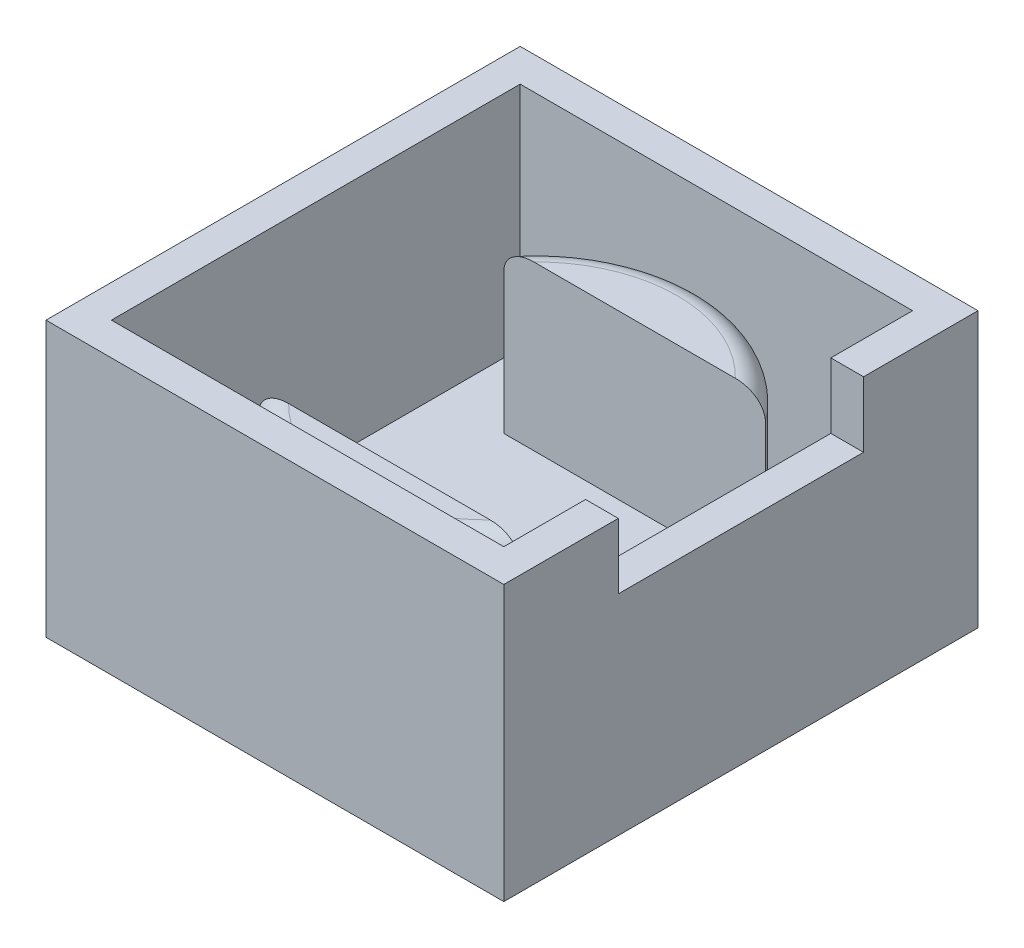
SolidWorks part; units mm, degrees
ref_plane "Front Plane" through (0, 0, 0) normal (0, 0, 1) x (1, 0, 0)
ref_plane "Top Plane" through (0, 0, 0) normal (0, 1, 0) x (1, 0, 0)
ref_plane "Right Plane" through (0, 0, 0) normal (1, 0, 0) x (0, 0, -1)
sketch "Sketch1" plane through (0, 0, 0) normal (0, 1, 0) x (1, 0, 0)
  line L1 (0, 0) -> (30.48, 0)
  line L2 (0, 0) -> (0, 31.75)
  line L3 (0, 31.75) -> (30.48, 31.75)
  line L4 (30.48, 0) -> (30.48, 31.75)
  dimension "D1" = 31.75
  dimension "D2" = 30.48
extrude "Boss-Extrude1" add sketch "Sketch1" along normal blind 3.556
sketch "Sketch2" plane through (0, 3.556, 0) normal (0, 1, 0) x (1, 0, 0)
  line L0 (0, 31.75) -> (0, 0) construction
  line L1 (0, 25.4) -> (30.48, 25.4)
  line L2 (0, 25.4) -> (0, 6.35)
  line L3 (0, 6.35) -> (30.48, 6.35)
  line L4 (30.48, 25.4) -> (30.48, 6.35)
  line L5 (30.48, 0) -> (30.48, 31.75) construction
  line L6 (30.48, 25.4) -> (30.48, 31.75) construction
  line L7 (30.48, 0) -> (30.48, 6.35) construction
  line L8 (0, 15.875) -> (30.48, 15.875) construction
  arc A0 (5.08, 25.4) -> (25.4, 25.4) centre (15.24, 17.78) cw
  arc A1 (5.08, 6.35) -> (25.4, 6.35) centre (15.24, 13.97) ccw
  dimension "D1" = 19.05
  dimension "D2" = 7.62
extrude "Boss-Extrude2" add sketch "Sketch2" along normal blind 12.7 contours L3 A1 | A0 L1
sketch "Sketch4" plane through (0, 3.556, 0) normal (0, 1, 0) x (1, 0, 0)
  line L0 (0, 31.75) -> (0, 0) construction
  line L1 (-1.778, 33.528) -> (67.818, 33.528)
  line L2 (-1.778, 33.528) -> (-1.778, -39.878)
  line L3 (-1.778, -39.878) -> (67.818, -39.878)
  line L4 (67.818, 33.528) -> (67.818, -39.878)
  line L5 (30.48, 31.75) -> (0, 31.75) construction
  line L7 (0, 31.75) -> (66.04, 31.75)
  line L8 (0, 31.75) -> (0, -38.1)
  line L9 (0, -38.1) -> (66.04, -38.1)
  line L10 (66.04, 31.75) -> (66.04, -38.1)
  line L12 (17.145, -38.1) -> (17.145, -7.62)
  line L13 (17.145, -7.62) -> (48.895, -7.62)
  line L14 (48.895, -7.62) -> (48.895, -38.1)
  line L15 (33.02, -38.1) -> (33.02, 16.283) construction
  dimension "D1" = 69.596
  dimension "D2" = 73.406
  dimension "D3" = 1.778
  dimension "D4" = 1.778
  dimension "D5" = 1.778
  dimension "D6" = 1.778
  dimension "D7" = 15.875
  dimension "D8" = 15.875
  dimension "D9" = 30.48
extrude "Boss-Extrude3" add sketch "Sketch4" against normal blind 3.556
sketch "Sketch8" plane through (0, 3.556, 0) normal (0, 1, 0) x (1, 0, 0)
  line L0 (0, 31.75) -> (0, 27.178)
  line L1 (0, 0) -> (0, 31.75) construction
  line L2 (0, 27.178) -> (0, 4.572)
  line L3 (-1.778, 27.178) -> (-1.778, 33.528)
  line L4 (-1.778, 33.528) -> (32.258, 33.528)
  line L5 (32.258, 33.528) -> (32.258, -1.778)
  line L6 (32.258, -1.778) -> (-1.778, -1.778)
  line L7 (-1.778, -1.778) -> (-1.778, 4.572)
  line L8 (-1.778, 4.572) -> (-1.778, 27.178)
  line L9 (0, 4.572) -> (0, 0)
  line L10 (0, 0) -> (30.48, 0)
  line L11 (30.48, 0) -> (30.48, 31.75)
  line L12 (30.48, 31.75) -> (0, 31.75)
  dimension "D1" = 1.778
  dimension "D2" = 1.778
  dimension "D3" = 1.778
  dimension "D4" = 1.778
  dimension "D5" = 1.778
  dimension "D6" = 6.35
  dimension "D7" = 6.35
extrude "Boss-Extrude5" add sketch "Sketch8" along normal blind 12.7 contours L5 L6 L7 L9 L10 L11 L12 L0 L3 L4
ref_plane "Plane2" through (0, 0, 3.175) normal (0, 0, -1) x (-1, 0, 0)
ref_plane "Plane1" through (33.02, 0, 0) normal (1, 0, 0) x (0, 0, -1)
mirror "Mirror1" about plane through (0, 0, 3.175) normal (0, 0, -1) of "Boss-Extrude5"
mirror "Mirror2" about plane through (33.02, 0, 0) normal (1, 0, 0) of "Mirror1", "Boss-Extrude5"
mirror "Mirror3" about plane through (0, 0, 3.175) normal (0, 0, -1) of "Boss-Extrude2"
mirror "Mirror4" about plane through (33.02, 0, 0) normal (1, 0, 0) of "Mirror3", "Boss-Extrude2"
fillet "Fillet5" radius 1.778 8 edges at (50.8, 16.256, 36.83) (15.24, 16.256, 36.83) (15.24, 16.256, 7.62) (15.24, 16.256, -1.27) (15.24, 16.256, -30.48) (50.8, 16.256, -30.48) (50.8, 16.256, -1.27) (50.8, 16.256, 7.62)
sketch "Sketch9" plane through (0, 16.256, 0) normal (0, 1, 0) x (1, 0, 0)
  line L1 (32.258, 33.528) -> (33.782, 33.528)
  line L2 (32.258, 33.528) -> (32.258, -39.878)
  line L3 (32.258, -39.878) -> (33.782, -39.878)
  line L4 (33.782, 33.528) -> (33.782, -39.878)
  line L5 (-1.778, -1.778) -> (67.818, -1.778)
  line L6 (-1.778, -1.778) -> (-1.778, -4.572)
  line L7 (-1.778, -4.572) -> (67.818, -4.572)
  line L8 (67.818, -1.778) -> (67.818, -4.572)
  line M47 (-1.778, -1.778) -> (32.258, -1.778)
  line M48 (32.258, -1.778) -> (32.258, 33.528)
extrude "Boss-Extrude7" add sketch "Sketch9" against normal up to body contours L5 L4 L1 M48 | L7 L2 L3 L4 | L2 L7 L4 L5 | L8 L5 L4 L7 | L6 L7 L2 M47
sketch "Sketch10" plane through (0, 16.256, 0) normal (0, 1, 0) x (1, 0, 0)
  line L0 (67.818, -4.572) -> (33.782, -4.572)
  line L1 (67.818, -39.878) -> (67.818, 33.528) construction
  line L2 (33.782, -4.572) -> (33.782, -39.878)
  line L3 (67.818, -39.878) -> (-1.778, -39.878) construction
  line L4 (33.782, -39.878) -> (-10.0613, -39.878)
  line L5 (-10.0613, -39.878) -> (-10.0613, 34.6908)
  line L6 (-10.0613, 34.6908) -> (71.0188, 34.6908)
  line L7 (71.0188, 34.6908) -> (71.0188, -4.572)
  line L8 (71.0188, -4.572) -> (67.818, -4.572)
  line L9 (35.56, -6.35) -> (35.56, -38.1) construction
  line L10 (66.04, -6.35) -> (35.56, -6.35) construction
  dimension "D1" = 1.778
  dimension "D2" = 1.778
extrude "Cut-Extrude1" cut sketch "Sketch10" against normal through all
sketch "Sketch11" plane through (0, 16.256, 0) normal (0, 1, 0) x (1, 0, 0)
  line L0 (33.02, -3.81) -> (33.02, -40.64)
  line L1 (33.782, -4.572) -> (67.818, -4.572)
  line L2 (33.782, -4.572) -> (33.782, -39.878)
  line L3 (33.782, -39.878) -> (67.818, -39.878)
  line L4 (67.818, -4.572) -> (67.818, -39.878)
  line L5 (33.02, -40.64) -> (68.58, -40.64)
  line L6 (68.58, -3.81) -> (68.58, -40.64)
  line L7 (33.02, -3.81) -> (68.58, -3.81)
  dimension "D1" = 0.762
extrude "Boss-Extrude8" add sketch "Sketch11" against normal up to surface (16.256 mm away) up to face at (50.8, 0, 22.225)
sketch "Sketch12" plane through (0, 16.256, 0) normal (0, 1, 0) x (1, 0, 0)
  line L0 (66.04, -12.7) -> (68.58, -12.7)
  line L1 (35.56, -6.35) -> (66.04, -6.35)
  line L2 (35.56, -6.35) -> (35.56, -38.1)
  line L3 (35.56, -38.1) -> (66.04, -38.1)
  line L4 (66.04, -6.35) -> (66.04, -12.7)
  line L5 (68.58, -40.64) -> (33.02, -40.64)
  line L6 (68.58, -40.64) -> (68.58, -31.75)
  line L7 (68.58, -3.81) -> (33.02, -3.81)
  line L8 (33.02, -40.64) -> (33.02, -3.81)
  line L9 (66.04, -31.75) -> (68.58, -31.75)
  line L10 (66.04, -22.225) -> (68.58, -22.225) construction
  line L11 (66.04, -31.75) -> (66.04, -38.1)
  line L12 (68.58, -12.7) -> (68.58, -3.81)
  dimension "D1" = 19.05
  dimension "D2" = 9.525
extrude "Boss-Extrude9" add sketch "Sketch12" along normal blind 5.08
